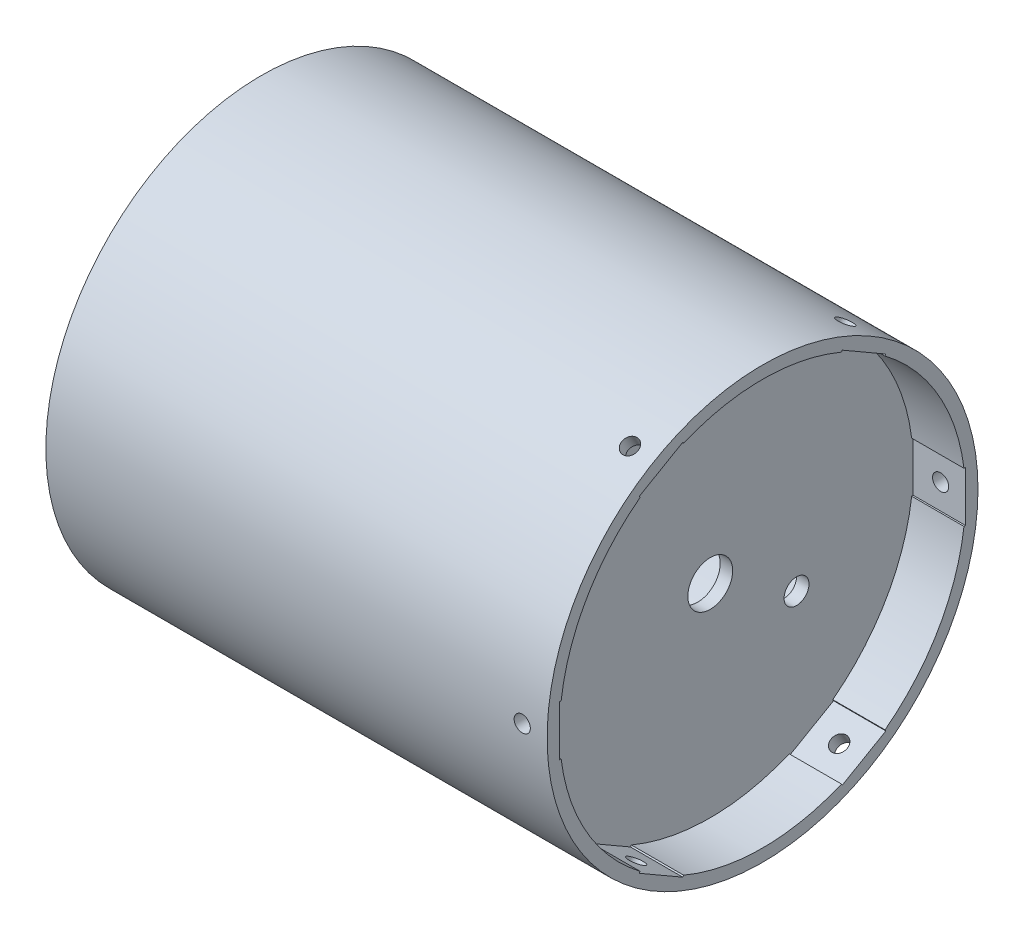
SolidWorks part; units mm, degrees
ref_plane "Płaszczyzna przednia" through (0, 0, 0) normal (0, 0, 1) x (1, 0, 0)
ref_plane "Płaszczyzna górna" through (0, 0, 0) normal (0, 1, 0) x (1, 0, 0)
ref_plane "Płaszczyzna prawa" through (0, 0, 0) normal (1, 0, 0) x (0, 0, -1)
sketch "Szkic1" plane through (0, 0, 0) normal (0, 0, 1) x (1, 0, 0)
  line L0 (5, 86.5) -> (26, 86.5)
  line L1 (0, 0) -> (5, 0)
  line L2 (0, 0) -> (0, 86.5)
  line L3 (0, 86.5) -> (5, 86.5)
  line L4 (5, 0) -> (5, 86.5)
  line L5 (5, 0) -> (-145.1472, 0)
  line L6 (26, 86.5) -> (-175.265, 86.5)
  line L7 (26, 86.5) -> (26, 81.5)
  line L8 (26, 81.5) -> (-175.265, 81.5)
  line L9 (-175.265, 86.5) -> (-175.265, 81.5)
revolve "Obrót1" add sketch "Szkic1" angle 360 about L5
sketch "Szkic7" plane through (0, 0, 0) normal (0, 0, 1) x (1, 0, 0)
  line L0 (26, 0) -> (16, 0)
  line L1 (26, -86.5) -> (26, 86.5) construction
  circle A0 centre (16, 0) radius 3.25
extrude "Wytnij-wyciągnięcie1" cut sketch "Szkic7" along normal blind 100
pattern_circular "Szyk kołowy1" count 6 over 360 about axis through (26, 0, 0) along (1, 0, 0) of "Wytnij-wyciągnięcie1"
sketch "Szkic9" plane through (26, 0, 0) normal (1, 0, 0) x (0, 0, -1)
  line L0 (-81.5, 0) -> (-81.5, 10.1)
  line L1 (-81.5, 10.1) -> (-77.6825, 10.1)
  line L2 (-81.5, 0) -> (-81.5, -10.1)
  line L3 (-81.5, -10.1) -> (-77.6825, -10.1)
  line L4 (-77.6825, -10.1) -> (-77.6825, 10.1)
  circle A0 centre (0, 0) radius 81.5 construction
  circle A1 centre (0, 0) radius 81.5 construction
extrude "Wytnij-wyciągnięcie3" cut sketch "Szkic9" against normal up to surface (21 mm away) up to face at (5, 0, -81.5)
pattern_circular "Szyk kołowy2" count 6 over 360 about axis through (0, 0, 0) along (1, 0, 0) of "Wytnij-wyciągnięcie3"
sketch "Szkic8" plane through (5, 0, 0) normal (1, 0, 0) x (0, 0, -1)
  line L0 (0, 0) -> (0, -50)
  line L1 (0, 0) -> (-40, 0)
  line L4 (0, 0) -> (34.641, -20)
  circle A3 centre (0, 0) radius 9
  circle A5 centre (34.641, -20) radius 5
extrude "Wytnij-wyciągnięcie2" cut sketch "Szkic8" against normal up to body
